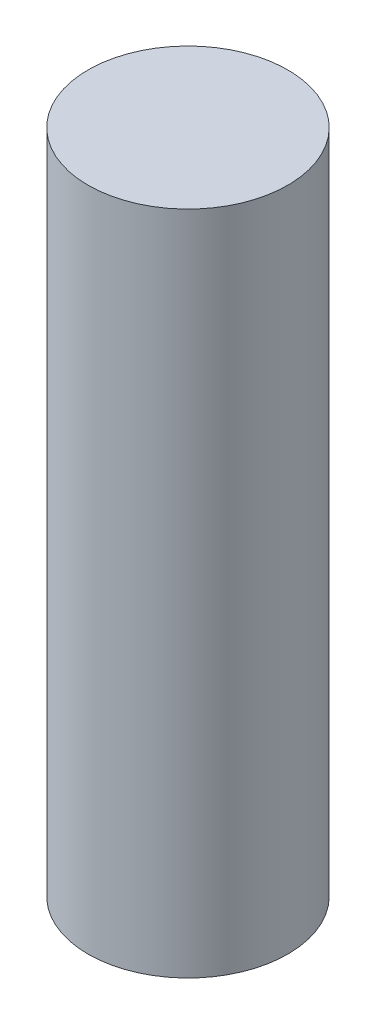
SolidWorks part; units mm, degrees
material "CP-Ti comercialmente puro UNS R50400 (SS)"
ref_plane "Plano frontal" through (0, 0, 0) normal (0, 0, 1) x (1, 0, 0)
ref_plane "Plano superior" through (0, 0, 0) normal (0, 1, 0) x (1, 0, 0)
ref_plane "Plano direito" through (0, 0, 0) normal (1, 0, 0) x (0, 0, -1)
sketch "Esboço1" plane through (0, 0, 0) normal (0, 1, 0) x (1, 0, 0)
  circle A0 centre (0, 0) radius 15
  dimension "D1" = 30
extrude "Ressalto-extrusão1" add sketch "Esboço1" along normal blind 100
